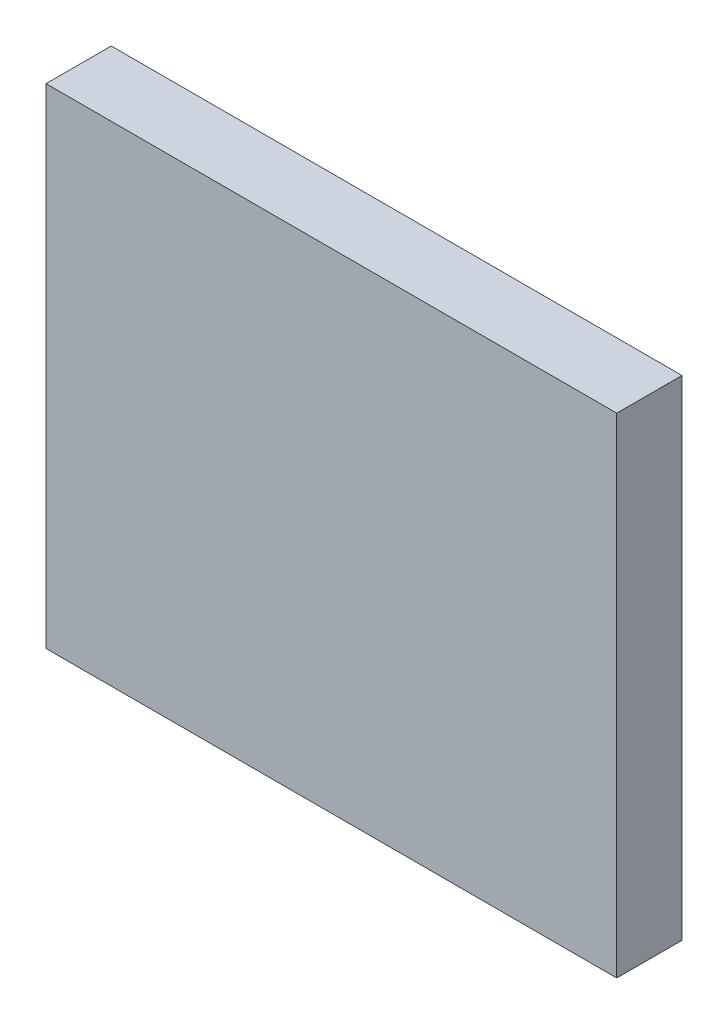
SolidWorks part; units mm, degrees
ref_plane "Front Plane" through (0, 0, 0) normal (0, 0, 1) x (1, 0, 0)
ref_plane "Top Plane" through (0, 0, 0) normal (0, 1, 0) x (1, 0, 0)
ref_plane "Right Plane" through (0, 0, 0) normal (1, 0, 0) x (0, 0, -1)
sketch "Sketch1" plane through (0, 0, 0) normal (0, 0, 1) x (1, 0, 0)
  line L1 (0, 0) -> (35, 0)
  line L2 (0, 0) -> (0, 30)
  line L3 (0, 30) -> (35, 30)
  line L4 (35, 0) -> (35, 30)
  dimension "D1" = 30
  dimension "D2" = 35
extrude "Boss-Extrude1" add sketch "Sketch1" along normal blind 4
